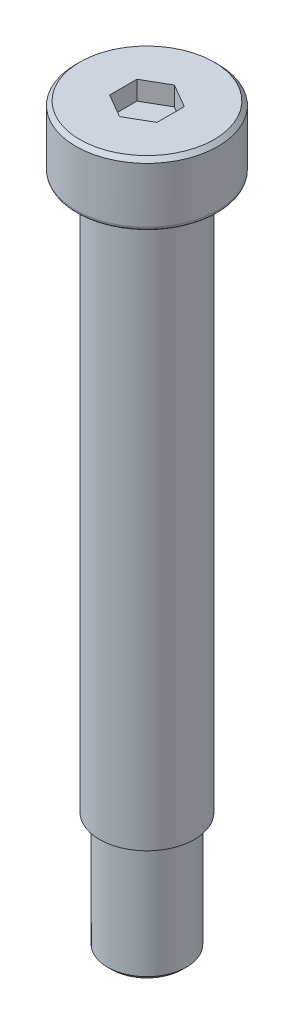
SolidWorks part; units mm, degrees
material "Plain Carbon Steel"
ref_plane "Front Plane" through (0, 0, 0) normal (0, 0, 1) x (1, 0, 0)
ref_plane "Top Plane" through (0, 0, 0) normal (0, 1, 0) x (1, 0, 0)
ref_plane "Right Plane" through (0, 0, 0) normal (1, 0, 0) x (0, 0, -1)
sketch "Sketch1" plane through (0, 0, 0) normal (0, 0, 1) x (1, 0, 0)
  line L0 (0, 0) -> (9, 0)
  line L1 (9, 0) -> (9, -8)
  line L2 (9, -8) -> (5.75, -8)
  line L3 (5.75, -8) -> (5.75, -8.5)
  line L4 (5.75, -8.5) -> (6, -8.5)
  line L5 (6, -8.5) -> (6, -78)
  line L6 (6, -78) -> (5, -78)
  line L7 (5, -78) -> (5, -93)
  line L8 (5, -93) -> (0, -93)
  line L9 (0, -93) -> (0, 0)
  line L10 (0, 5) -> (0, -98) construction
  dimension "D1" = 5
  dimension "D2" = 5
  dimension "D3" = 10
  dimension "D4" = 12
  dimension "D5" = 0.25
  dimension "D6" = 18
  dimension "D7" = 70
  dimension "D8" = 8
  dimension "D9" = 0.5
  dimension "D10" = 15
revolve "Revolve1" add sketch "Sketch1" angle 360 about L10
sketch "Sketch2" plane through (0, 0, 0) normal (0, 1, 0) x (1, 0, 0)
  line L1 (0, -3.4641) -> (3, -1.7321)
  line L2 (3, -1.7321) -> (3, 1.7321)
  line L3 (3, 1.7321) -> (0, 3.4641)
  line L4 (0, 3.4641) -> (-3, 1.7321)
  line L5 (-3, 1.7321) -> (-3, -1.7321)
  line L6 (-3, -1.7321) -> (0, -3.4641)
  circle A0 centre (0, 0) radius 3 construction
  dimension "D1" = 6
extrude "Cut-Extrude1" cut sketch "Sketch2" against normal blind 2.4
chamfer "Chamfer1" distance 0.5 angle 45 1 edges at (-9, 0, 0)
fillet "Fillet1" radius 0.5 1 edges at (-9, -8, 0)
chamfer "Chamfer2" distance 0.5 angle 45 1 edges at (-5, -93, 0)
